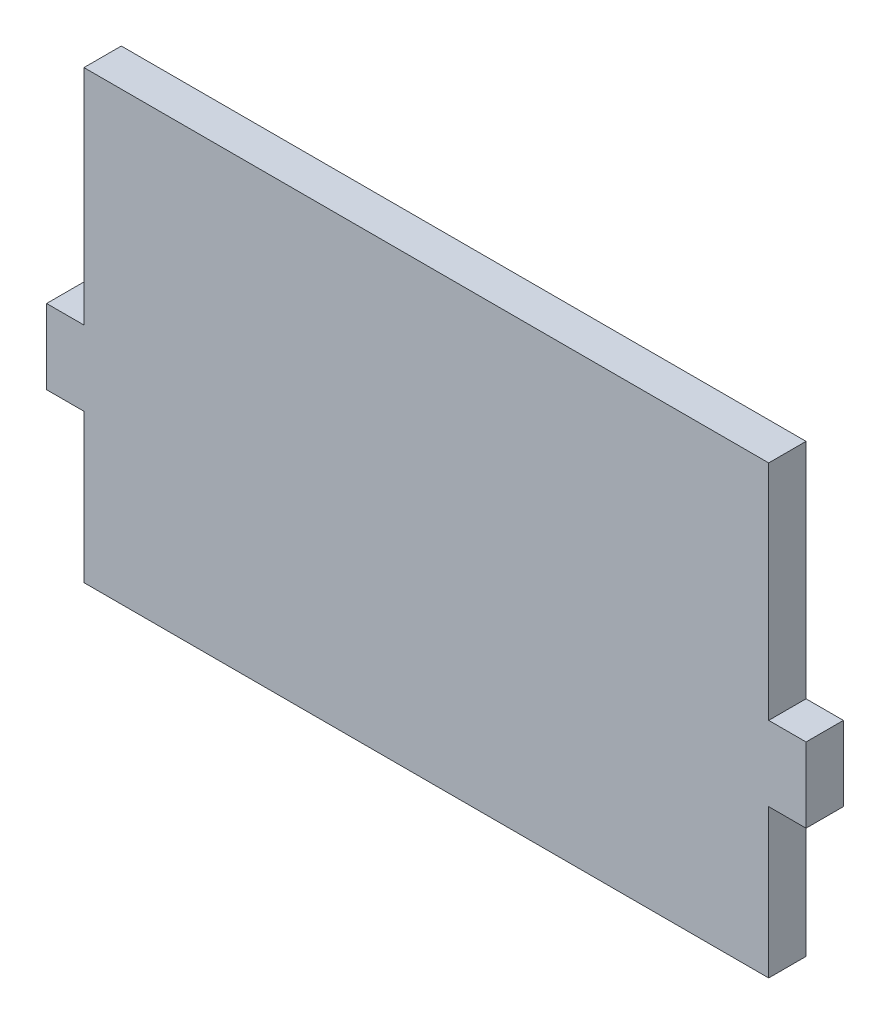
SolidWorks part; units mm, degrees
ref_plane "Přední rovina" through (0, 0, 0) normal (0, 0, 1) x (1, 0, 0)
ref_plane "Horní rovina" through (0, 0, 0) normal (0, 1, 0) x (1, 0, 0)
ref_plane "Pravá rovina" through (0, 0, 0) normal (1, 0, 0) x (0, 0, -1)
sketch "Skica1" plane through (0, 0, 0) normal (0, 0, 1) x (1, 0, 0)
  line L0 (55, -23.91) -> (55, -35.83)
  line L1 (0, 0) -> (55, 0)
  line L2 (0, 0) -> (0, -17.91)
  line L3 (0, -35.83) -> (55, -35.83)
  line L4 (55, 0) -> (55, -17.91)
  line L5 (0, -17.91) -> (-3, -17.91)
  line L6 (0, -23.91) -> (-3, -23.91)
  line L7 (-3, -17.91) -> (-3, -23.91)
  line L8 (55, -17.91) -> (58, -17.91)
  line L9 (55, -23.91) -> (58, -23.91)
  line L10 (58, -17.91) -> (58, -23.91)
  line L11 (0, -23.91) -> (0, -35.83)
  dimension "D1" = 55
  dimension "D2" = 35.83
  dimension "D3" = 17.91
  dimension "D4" = 0
  dimension "D5" = 6
  dimension "D6" = 6
  dimension "D7" = 3
  dimension "D8" = 3
extrude "Přidat vysunutím1" add sketch "Skica1" along normal blind 3
